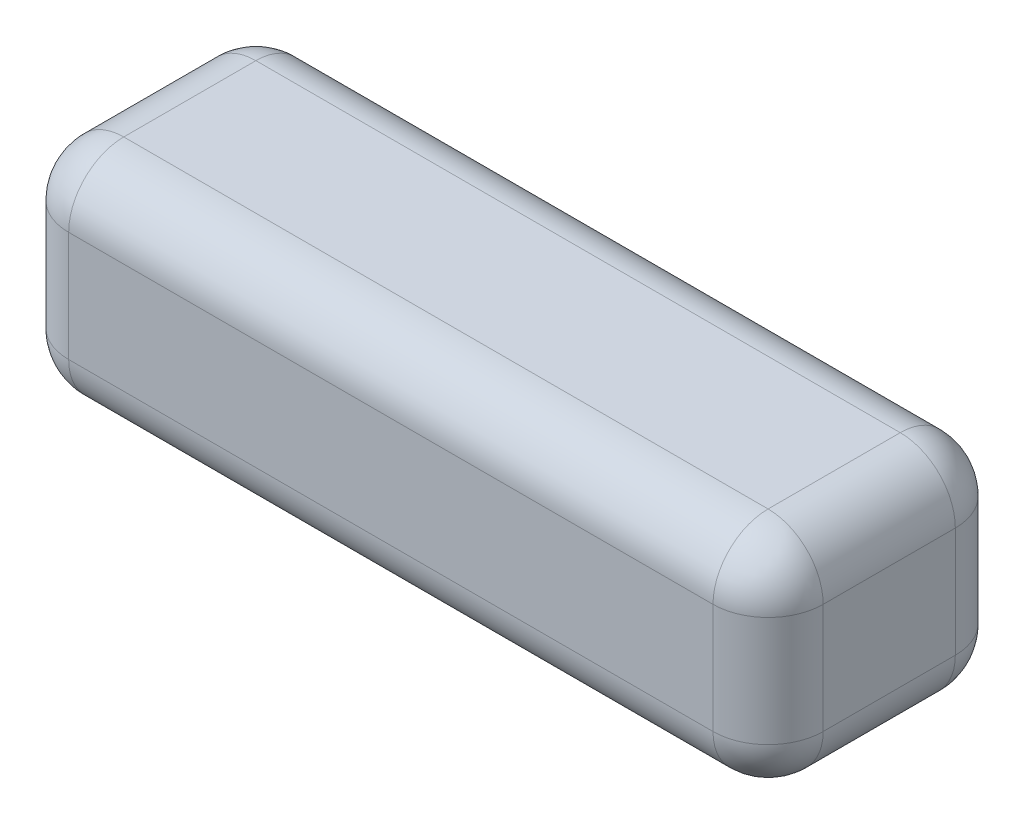
SolidWorks part; units mm, degrees
ref_plane "Front Plane" through (0, 0, 0) normal (0, 0, 1) x (1, 0, 0)
ref_plane "Top Plane" through (0, 0, 0) normal (0, 1, 0) x (1, 0, 0)
ref_plane "Right Plane" through (0, 0, 0) normal (1, 0, 0) x (0, 0, -1)
sketch "Sketch1" plane through (0, 0, 0) normal (0, 1, 0) x (1, 0, 0)
  line L1 (-32.6857, 18.3683) -> (104.3143, 18.3683)
  line L2 (-32.6857, 18.3683) -> (-32.6857, -25.6317)
  line L3 (-32.6857, -25.6317) -> (104.3143, -25.6317)
  line L4 (104.3143, 18.3683) -> (104.3143, -25.6317)
  dimension "D1" = 44
  dimension "D2" = 137
extrude "Boss-Extrude1" add sketch "Sketch1" along normal blind 40
fillet "Fillet1" radius 10 12 edges at (-32.6857, 0, 3.6317) (104.3143, 0, 3.6317) (104.3143, 20, -18.3683) (35.8143, 0, -18.3683) (-32.6857, 20, -18.3683) (-32.6857, 20, 25.6317) (35.8143, 0, 25.6317) (104.3143, 20, 25.6317) (104.3143, 40, 3.6317) (35.8143, 40, -18.3683) (-32.6857, 40, 3.6317) (35.8143, 40, 25.6317)
